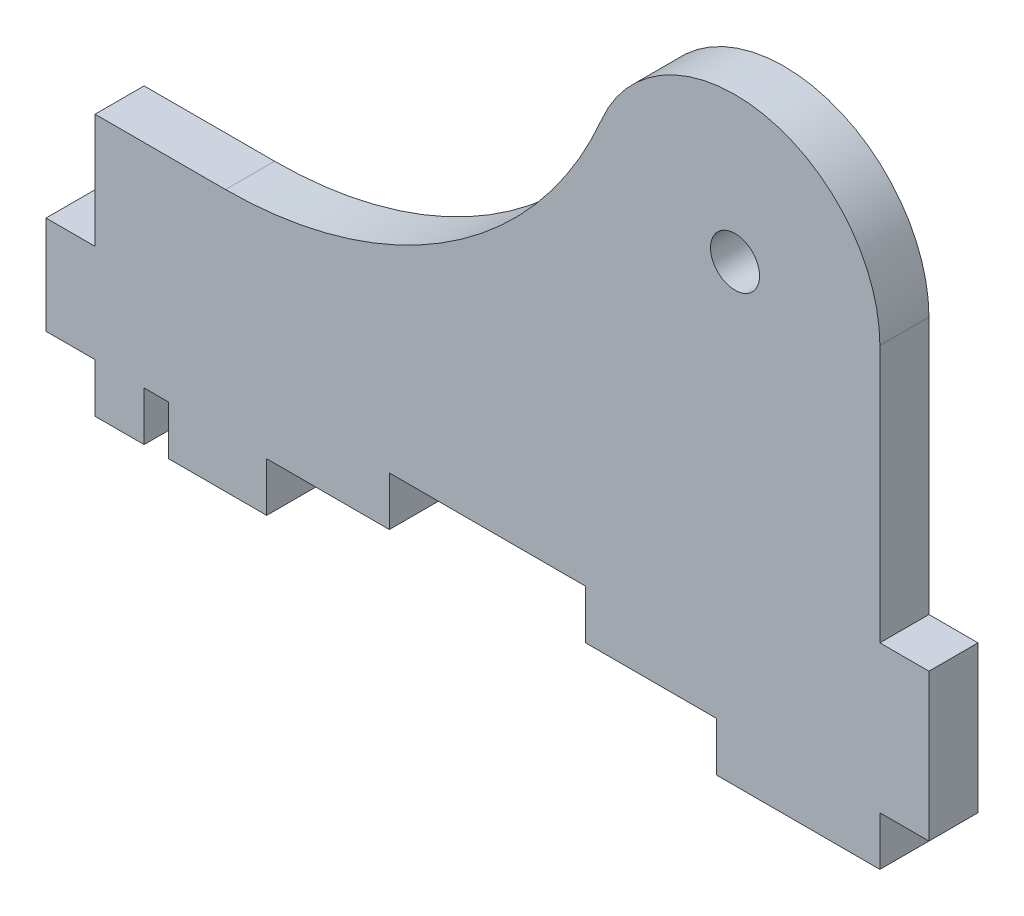
SolidWorks part; units mm, degrees
material "Acrílico (médio-alto impacto)"
ref_plane "Plano frontal" through (0, 0, 0) normal (0, 0, 1) x (1, 0, 0)
ref_plane "Plano superior" through (0, 0, 0) normal (0, 1, 0) x (1, 0, 0)
ref_plane "Plano direito" through (0, 0, 0) normal (1, 0, 0) x (0, 0, -1)
sketch "Esboço1" plane through (0, 0, 0) normal (0, 0, 1) x (1, 0, 0)
  line L0 (0, 0) -> (48, 0)
  line L1 (48, 0) -> (48, 24.75)
  line L3 (7.9801, 13) -> (0, 13)
  line L4 (0, 13) -> (0, 0)
  line L5 (39.14, 24.75) -> (48, 24.75) construction
  arc A0 (48, 24.75) -> (30.9865, 28.2171) centre (39.14, 24.75) ccw
  arc A1 (30.9865, 28.2171) -> (7.9801, 13) centre (7.9801, 38) cw
  dimension "D4" = 8.86
  dimension "D5" = 25
  dimension "D1" = 13
  dimension "D2" = 48
  dimension "D3" = 24.75
  dimension "D6" = 8.86
  dimension "D7" = 33.61
sketch "Esboço2" plane through (0, 0, 0) normal (0, 0, 1) x (1, 0, 0)
  line L0 (0, 0) -> (48, 0) construction
  line L1 (30, 0) -> (18, 0)
  line L2 (30, 0) -> (30, 3)
  line L3 (30, 3) -> (18, 3)
  line L4 (18, 0) -> (18, 3)
  line L5 (24, 3) -> (24, 0) construction
  line L6 (48, 0) -> (48, 24.75) construction
  line L7 (0, 13) -> (0, 0) construction
  dimension "D1" = 3
  dimension "D2" = 12
sketch "Esboço5" plane through (0, 0, 0) normal (0, 0, 1) x (1, 0, 0)
  line L0 (30, 0) -> (30, 3) construction
  line L1 (48, 0) -> (51, 0)
  line L2 (48, 0) -> (48, 9)
  line L3 (48, 9) -> (51, 9)
  line L4 (51, 0) -> (51, 9)
  line L6 (0, 0) -> (-3, 0)
  line L7 (0, 0) -> (0, 6)
  line L8 (0, 6) -> (-3, 6)
  line L9 (-3, 0) -> (-3, 6)
  line L10 (0, 0) -> (3, 0)
  line L11 (0, 0) -> (0, -3)
  line L12 (0, -3) -> (3, -3)
  line L13 (3, 0) -> (3, -3)
  line L14 (4.5, 0) -> (10.5, 0)
  line L15 (4.5, 0) -> (4.5, -3)
  line L16 (4.5, -3) -> (10.5, -3)
  line L17 (10.5, 0) -> (10.5, -3)
  line L18 (48, 0) -> (38, 0)
  line L19 (48, 0) -> (48, -3)
  line L20 (48, -3) -> (38, -3)
  line L21 (38, 0) -> (38, -3)
  dimension "D1" = 9
  dimension "D2" = 6
  dimension "D3" = 1.5
  dimension "D4" = 3
  dimension "D5" = 6
  dimension "D6" = 10
extrude "Ressalto-extrusão1" add sketch "Esboço1" against normal blind 3
extrude "Corte-extrusão1" cut sketch "Esboço2" against normal through all contours L3 L4 L1 L2
hole_wizard "Furo de diâmetro Ø3.0 (3)1" positions "Esboço3" profile "Esboço4" hole size "Ø3.0" standard "ISO" end condition through all
sketch "Esboço3" plane through (0, 0, 0) normal (0, 0, 1) x (1, 0, 0)
  point P0 (39.14, 24.75)
sketch "Esboço4" plane through (39.14, 24.75, 0) normal (1, 0, 0) x (0, -1, 0)
  line L0 (0, 0) -> (0, 3)
  line L1 (0, 3) -> (1.5, 3)
  line L2 (1.5, 3) -> (1.5, 0)
  line L5 (1.5, 0) -> (0, 0)
  line L11 (0, -6.35) -> (0, 107.95) construction
  dimension "Thru Hole Dia." = 3
  dimension "Thru Hole Depth" = 3
extrude "Ressalto-extrusão2" add sketch "Esboço5" against normal through all contours L9 L6 L7 L8 | L13 L10 L11 L12 | L17 L14 L15 L16 | L1 L4 L3 L2 | L18 L21 L20 L19
